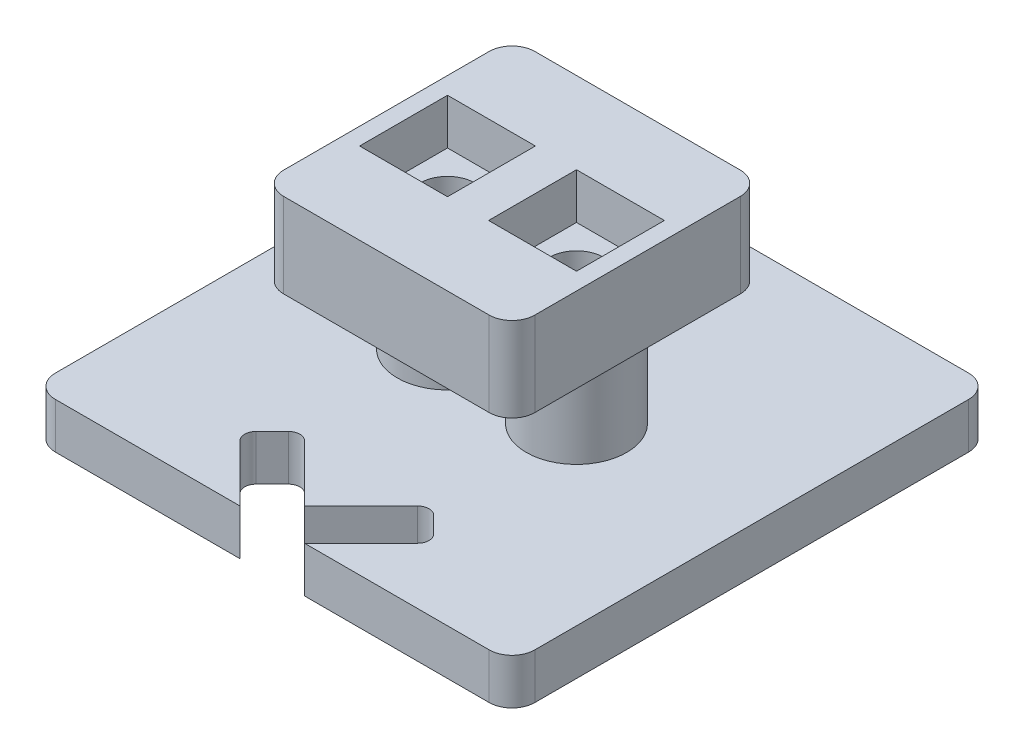
SolidWorks part; units mm, degrees
ref_plane "Front Plane" through (0, 0, 0) normal (0, 0, 1) x (1, 0, 0)
ref_plane "Top Plane" through (0, 0, 0) normal (0, 1, 0) x (1, 0, 0)
ref_plane "Right Plane" through (0, 0, 0) normal (1, 0, 0) x (0, 0, -1)
sketch "Sketch1" plane through (0, 0, 0) normal (0, 1, 0) x (1, 0, 0)
  line L1 (-5.5, -5.5) -> (5.5, -5.5)
  line L2 (-5.5, -5.5) -> (-5.5, 5.5)
  line L3 (-5.5, 5.5) -> (5.5, 5.5)
  line L4 (5.5, -5.5) -> (5.5, 5.5)
  line L5 (-5.5, -5.5) -> (5.5, 5.5) construction
  line L6 (-5.5, 5.5) -> (5.5, -5.5) construction
  point P0 (0, 0)
  dimension "D1" = 11
  dimension "D2" = 11
extrude "Boss-Extrude1" add sketch "Sketch1" along normal blind 3.7
fillet "Fillet1" radius 1 4 edges at (-5.5, 1.85, -5.5) (-5.5, 1.85, 5.5) (5.5, 1.85, -5.5) (5.5, 1.85, 5.5)
sketch "Sketch2" plane through (0, 3.7, 0) normal (0, 1, 0) x (1, 0, 0)
  line L0 (-2.825, 0) -> (2.825, 0) construction
  line L2 (-4.75, -1.925) -> (-0.9, -1.925)
  line L3 (-4.75, -1.925) -> (-4.75, 1.925)
  line L4 (-4.75, 1.925) -> (-0.9, 1.925)
  line L5 (-0.9, -1.925) -> (-0.9, 1.925)
  line L6 (-4.75, -1.925) -> (-0.9, 1.925) construction
  line L7 (-4.75, 1.925) -> (-0.9, -1.925) construction
  line L8 (0.9, -1.925) -> (4.75, -1.925)
  line L9 (0.9, -1.925) -> (0.9, 1.925)
  line L10 (0.9, 1.925) -> (4.75, 1.925)
  line L11 (4.75, -1.925) -> (4.75, 1.925)
  line L12 (0.9, -1.925) -> (4.75, 1.925) construction
  line L13 (0.9, 1.925) -> (4.75, -1.925) construction
  point P4 (0, 0)
  dimension "D1" = 3.85
  dimension "D2" = 3.85
  dimension "D3" = 3.85
  dimension "D4" = 3.85
  dimension "D5" = 5.65
extrude "Cut-Extrude1" cut sketch "Sketch2" against normal blind 2
sketch "Sketch4" plane through (0, 0, 0) normal (0, -1, 0) x (-1, 0, 0)
  line L0 (2.825, 0) -> (-2.825, 0) construction
  circle A0 centre (2.825, 0) radius 2.2
  circle A1 centre (-2.825, 0) radius 2.2
  point P8 (0, 0)
  dimension "D1" = 5.65
  dimension "D2" = 4.4
  dimension "D3" = 4.4
extrude "Boss-Extrude2" add sketch "Sketch4" along normal blind 6
sketch "Sketch5" plane through (0, -6, 0) normal (0, -1, 0) x (-1, 0, 0)
  line L1 (9.5, 10.5) -> (-9.5, 10.5)
  line L2 (10.5, 9.5) -> (10.5, -9.5)
  line L3 (9.5, -10.5) -> (-9.5, -10.5)
  line L4 (-10.5, 9.5) -> (-10.5, -9.5)
  line L5 (10.5, 10.5) -> (-10.5, -10.5) construction
  line L6 (10.5, -10.5) -> (-10.5, 10.5) construction
  arc A0 (10.5, -9.5) -> (9.5, -10.5) centre (9.5, -9.5) cw
  arc A1 (-10.5, -9.5) -> (-9.5, -10.5) centre (-9.5, -9.5) ccw
  arc A2 (-9.5, 10.5) -> (-10.5, 9.5) centre (-9.5, 9.5) ccw
  arc A3 (9.5, 10.5) -> (10.5, 9.5) centre (9.5, 9.5) cw
  point P0 (0, 0)
  dimension "D3" = 1
  dimension "D1" = 21
  dimension "D2" = 21
extrude "Boss-Extrude3" add sketch "Sketch5" against normal blind 2
sketch "Sketch3" plane through (0, 3.7, 0) normal (0, 1, 0) x (1, 0, 0)
  line L0 (-2.825, 0) -> (2.825, 0) construction
  circle A0 centre (-2.825, 0) radius 1.2
  circle A1 centre (2.825, 0) radius 1.2
  point P8 (0, 0)
  dimension "D2" = 2.4
  dimension "D3" = 2.4
  dimension "D1" = 5.65
extrude "Cut-Extrude2" cut sketch "Sketch3" against normal through all
sketch "Sketch7" plane through (0, -4, 0) normal (0, 1, 0) x (1, 0, 0)
  line L0 (9.5, -10.5) -> (-9.5, -10.5) construction
  line L1 (2.8284, -14.7426) -> (4.2426, -13.3284)
  line L2 (2.8284, -14.7426) -> (-3.8891, -8.0251)
  line L3 (-3.8891, -7.318) -> (-3.182, -6.6109)
  line L4 (4.2426, -13.3284) -> (-2.4749, -6.6109)
  line L5 (2.8284, -14.7426) -> (-2.8284, -6.2574) construction
  line L6 (-4.2426, -7.6716) -> (4.2426, -13.3284) construction
  line L8 (-4.2426, -13.3284) -> (-2.8284, -14.7426)
  line L9 (-4.2426, -13.3284) -> (2.4749, -6.6109)
  line L10 (3.182, -6.6109) -> (3.8891, -7.318)
  line L11 (-2.8284, -14.7426) -> (3.8891, -8.0251)
  line L12 (-4.2426, -13.3284) -> (4.2426, -7.6716) construction
  line L13 (2.8284, -6.2574) -> (-2.8284, -14.7426) construction
  arc A0 (-2.4749, -6.6109) -> (-3.182, -6.6109) centre (-2.8284, -6.9645) ccw
  arc A1 (3.8891, -7.318) -> (3.8891, -8.0251) centre (3.5355, -7.6716) cw
  arc A2 (3.182, -6.6109) -> (2.4749, -6.6109) centre (2.8284, -6.9645) ccw
  arc A3 (-3.8891, -7.318) -> (-3.8891, -8.0251) centre (-3.5355, -7.6716) ccw
  point P0 (0, -10.5)
  point P7 (0, -10.5)
  point P12 (-1.4142, -10.5)
  point P13 (1.4142, -10.5)
  line M12 (-9.5, -10.5) -> (9.5, -10.5)
  dimension "D7" = 0.5
  dimension "D8" = 0.5
  dimension "D1" = 2
  dimension "D2" = 45
  dimension "D3" = 2
  dimension "D4" = 45
  dimension "D5" = 4
  dimension "D6" = 4
extrude "Cut-Extrude3" cut sketch "Sketch7" against normal through all contours L10 A2 L9 L4 L11 A1 | L3 A3 L2 L9 L4 A0 | L9 L4 M12
sketch "Sketch8" plane through (0, -6, 0) normal (0, -1, 0) x (1, 0, 0)
  circle A0 centre (-2.825, 0) radius 1.2
  circle A1 centre (-2.825, 0) radius 2.2
  circle A2 centre (2.825, 0) radius 1.2
  circle A3 centre (2.825, 0) radius 2.2
  dimension "D1" = 1
  dimension "D2" = 1
extrude "Boss-Extrude4" add sketch "Sketch8" along normal blind 4
equation "\"D2@Sketch2\"=\"D1@Sketch2\""
equation "\"D3@Sketch2\"=\"D1@Sketch2\""
equation "\"D4@Sketch2\"=\"D1@Sketch2\""
equation "\"D2@Sketch1\"=\"D1@Sketch1\""
equation "\"D3@Sketch3\"=\"D2@Sketch3\""
equation "\"D3@Sketch4\"=\"D2@Sketch4\""
equation "\"D2@Sketch5\"=\"D1@Sketch5\""
equation "\"D3@Sketch7\"=\"D1@Sketch7\""
equation "\"D6@Sketch7\"=\"D5@Sketch7\""
equation "\"D2@Sketch8\"=\"D1@Sketch8\""
